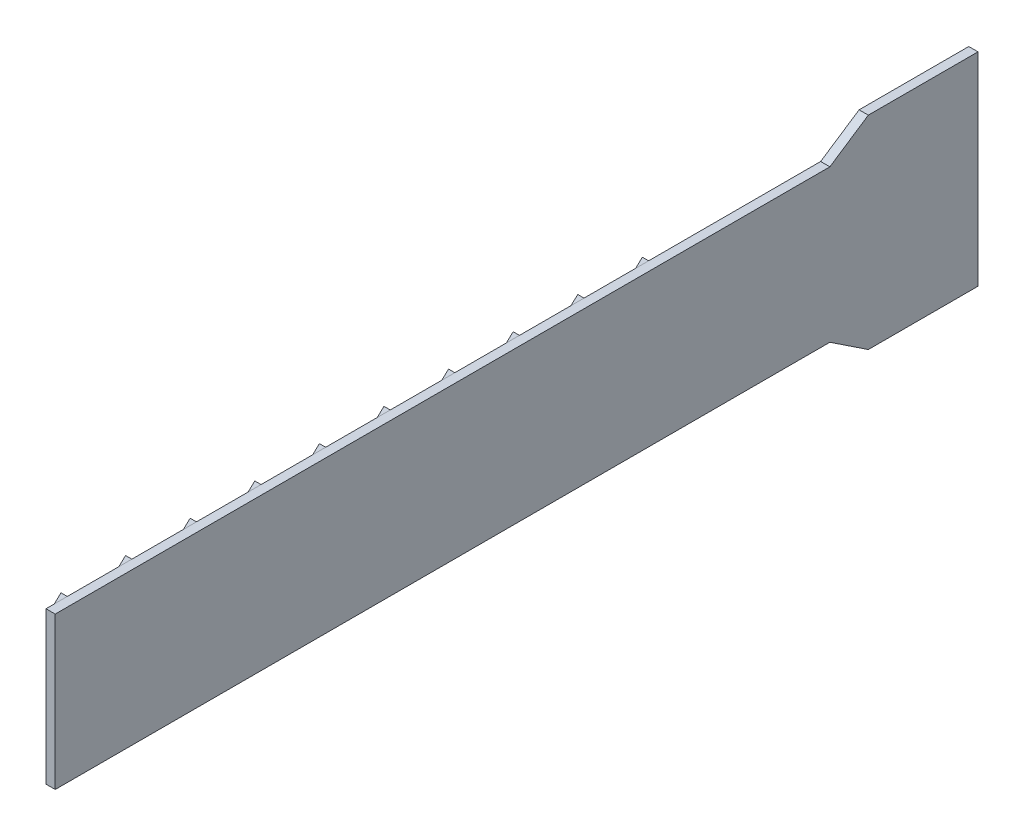
SolidWorks part; units mm, degrees
ref_plane "Front Plane" through (0, 0, 0) normal (0, 0, 1) x (1, 0, 0)
ref_plane "Top Plane" through (0, 0, 0) normal (0, 1, 0) x (1, 0, 0)
ref_plane "Right Plane" through (0, 0, 0) normal (1, 0, 0) x (0, 0, -1)
sketch "Sketch5" plane through (10, 0, 0) normal (1, 0, 0) x (0, 0, -1)
  line L0 (1000, 220) -> (1000, 0)
  line L1 (1000, 0) -> (881.1289, 0)
  line L2 (881.1289, 0) -> (839.4802, 27.6657)
  line L3 (839.4802, 27.6657) -> (0, 27.6657)
  line L4 (0, 27.6657) -> (0, 192.3343)
  line L5 (0, 192.3343) -> (839.4802, 192.3343)
  line L6 (839.4802, 192.3343) -> (881.1289, 220)
  line L7 (881.1289, 220) -> (1000, 220)
extrude "Boss-Extrude1" add sketch "Sketch5" along normal blind 10
sketch "Sketch6" plane through (0, 27.6657, 0) normal (0, -1, 0) x (-1, 0, 0)
  line L0 (-10, 23.7385) -> (-2.5, 23.7385)
  line L1 (-10, 0) -> (-10, 839.4802) construction
  line L2 (-2.5, 23.7385) -> (-10, 8.2591)
  line L3 (-10, 8.2591) -> (-10, 23.7385)
extrude "Boss-Extrude2" add sketch "Sketch6" against normal blind 164
pattern_linear "LPattern1" count 10 spacing 70 along (0, 0, -1) of "Boss-Extrude2"
